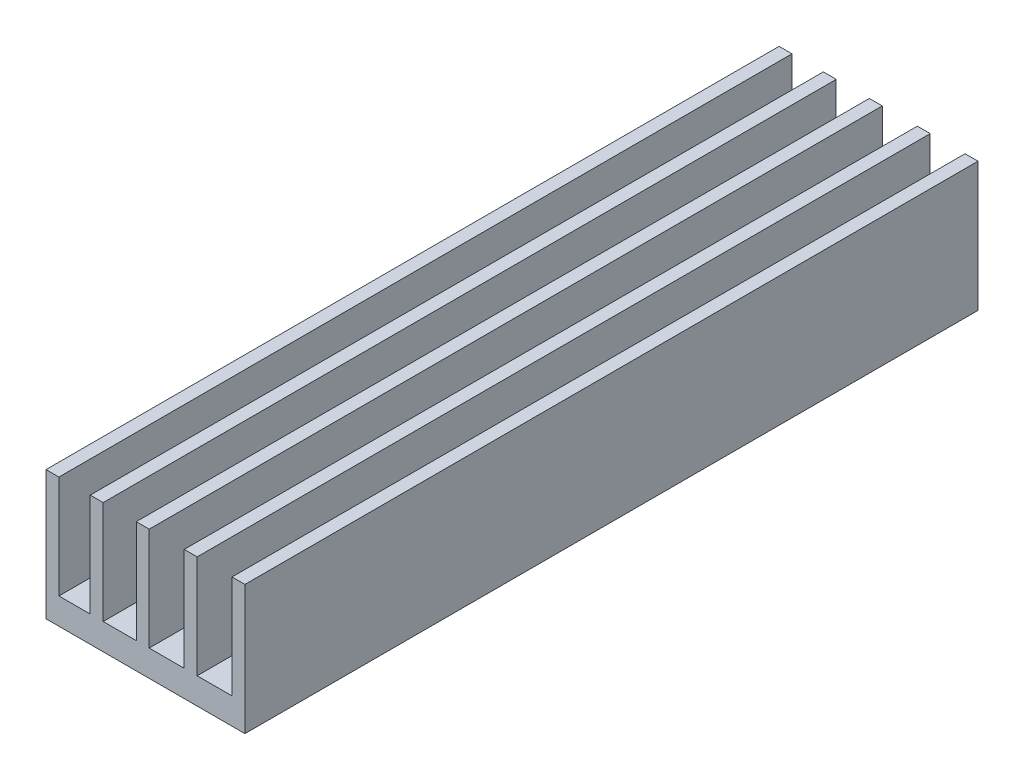
SolidWorks part; units mm, degrees
material "1060 Alloy"
ref_plane "Front Plane" through (0, 0, 0) normal (0, 0, 1) x (1, 0, 0)
ref_plane "Top Plane" through (0, 0, 0) normal (0, 1, 0) x (1, 0, 0)
ref_plane "Right Plane" through (0, 0, 0) normal (1, 0, 0) x (0, 0, -1)
sketch "Sketch1" plane through (0, 0, 0) normal (0, 0, 1) x (1, 0, 0)
  line L0 (0, 0) -> (25.019, 0)
  line L1 (0, 0) -> (0, 16.256)
  line L2 (0, 16.256) -> (1.6256, 16.256)
  line L3 (1.6256, 16.256) -> (1.6256, 3.302)
  line L4 (1.6256, 3.302) -> (5.5647, 3.302)
  line L5 (5.5647, 3.302) -> (5.5647, 16.256)
  line L6 (5.5647, 16.256) -> (7.1903, 16.256)
  line L7 (7.1903, 16.256) -> (7.1903, 3.302)
  line L8 (7.1903, 3.302) -> (11.352, 3.302)
  line L9 (11.352, 3.302) -> (11.352, 16.256)
  line L10 (11.352, 16.256) -> (12.9776, 16.256)
  line L11 (12.9776, 16.256) -> (12.9776, 3.302)
  line L12 (12.9776, 3.302) -> (17.3874, 3.302)
  line L13 (17.3874, 3.302) -> (17.3874, 16.256)
  line L14 (17.3874, 16.256) -> (19.013, 16.256)
  line L15 (19.013, 16.256) -> (19.013, 3.302)
  line L16 (19.013, 3.302) -> (23.3934, 3.302)
  line L17 (23.3934, 3.302) -> (23.3934, 16.256)
  line L18 (23.3934, 16.256) -> (25.019, 16.256)
  line L19 (25.019, 16.256) -> (25.019, 0)
  dimension "D1" = 25.019
  dimension "D2" = 16.256
  dimension "D3" = 3.302
  dimension "D4" = 1.6256
extrude "Extrude1" add sketch "Sketch1" against normal blind 92.202
hole_wizard "#4-40 Tapped Hole1" positions "Sketch3" profile "Sketch2" tap size "#4-40" standard "Ansi Inch"
sketch "Sketch3" plane through (0, 0, 0) normal (0, -1, 0) x (1, 0, 0)
  line L0 (0, -46.101) -> (38.9511, -46.101) construction
  line L1 (0, -92.202) -> (0, 0) construction
  point P0 (9.525, -25.4)
  point P1 (9.525, -78.74)
  dimension "D1" = 25.4
  dimension "D2" = 9.525
  dimension "D3" = 53.34
sketch "Sketch2" plane through (9.525, 0, -25.4) normal (1, 0, 0) x (0, 0, -1)
  line L0 (0, 0) -> (0, 8.2738)
  line L1 (0, 8.2738) -> (1.1303, 7.5946)
  line L2 (1.1303, 7.5946) -> (1.1303, 0)
  line L5 (1.1303, 0) -> (0, 0)
  line L10 (0, 8.2738) -> (-1.1303, 7.5946) construction
  line L11 (0, -6.35) -> (0, 107.95) construction
  dimension "Tap Drill Dia." = 2.2606
  dimension "Tap Drill Depth" = 7.5946
  dimension "Drill Angle" = 118
cosmetic thread "Hole Thread1" parameters "D1"=5.6896, "D2"=2.8448
cosmetic thread "Hole Thread2" parameters "D1"=5.6896, "D2"=2.8448
